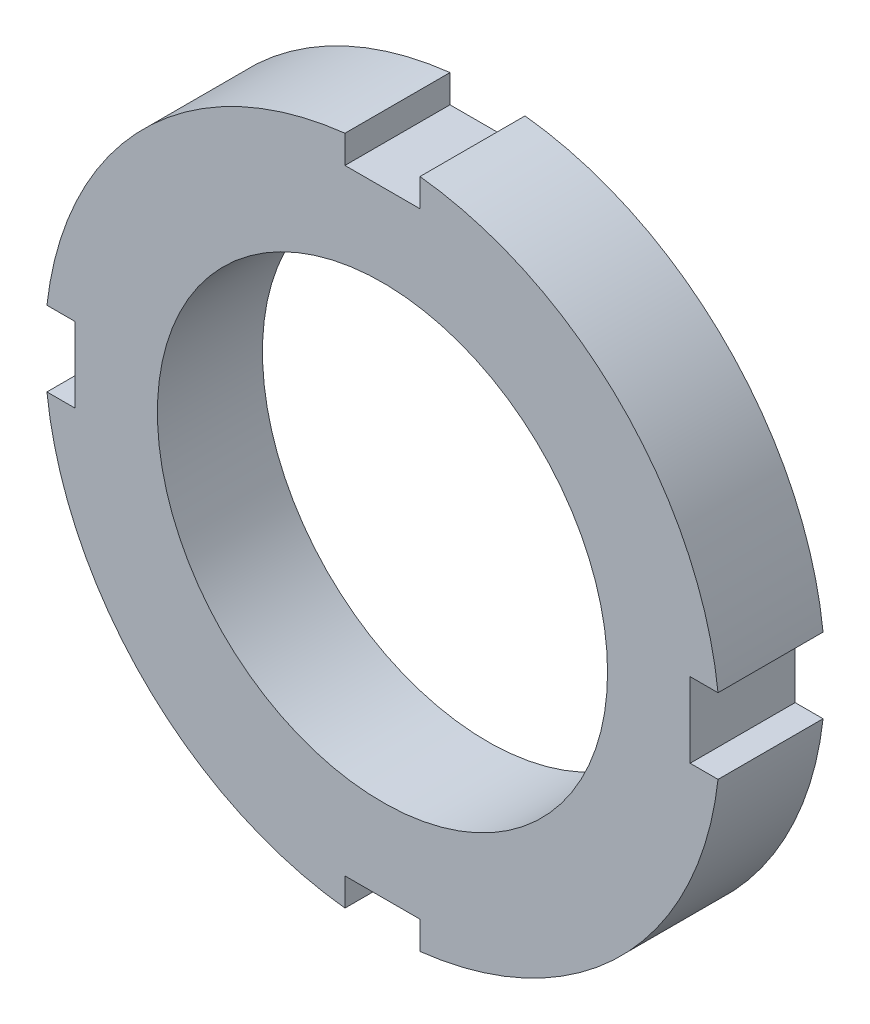
SolidWorks part; units mm, degrees
material "1.0503 (C45)"
ref_plane "Front Plane" through (0, 0, 0) normal (0, 0, 1) x (1, 0, 0)
ref_plane "Top Plane" through (0, 0, 0) normal (0, 1, 0) x (1, 0, 0)
ref_plane "Right Plane" through (0, 0, 0) normal (1, 0, 0) x (0, 0, -1)
sketch "Sketch1" plane through (0, 0, 0) normal (0, 1, 0) x (1, 0, 0)
  line L0 (15, 89) -> (22.5, 89)
  line L1 (22.5, 89) -> (22.5, 96)
  line L2 (22.5, 96) -> (15, 96)
  line L3 (15, 96) -> (15, 89)
  line L4 (0, -150) -> (0, 150) construction
revolve "REV_KM6_M30x1.5_45x7" add sketch "Sketch1" angle 360 about L4
sketch "Sketch2" plane through (0, 0, 0) normal (0, 0, 1) x (1, 0, 0)
  line L1 (20.5, -2.5) -> (23.5, -2.5)
  line L2 (20.5, -2.5) -> (20.5, 2.5)
  line L3 (20.5, 2.5) -> (23.5, 2.5)
  line L4 (23.5, -2.5) -> (23.5, 2.5)
  line L6 (-23.5, -2.5) -> (-20.5, -2.5)
  line L7 (-23.5, -2.5) -> (-23.5, 2.5)
  line L8 (-23.5, 2.5) -> (-20.5, 2.5)
  line L9 (-20.5, -2.5) -> (-20.5, 2.5)
  line L11 (-2.5, 20.5) -> (2.5, 20.5)
  line L12 (-2.5, 20.5) -> (-2.5, 23.5)
  line L13 (-2.5, 23.5) -> (2.5, 23.5)
  line L14 (2.5, 20.5) -> (2.5, 23.5)
  line L16 (-2.5, -23.5) -> (2.5, -23.5)
  line L17 (-2.5, -23.5) -> (-2.5, -20.5)
  line L18 (-2.5, -20.5) -> (2.5, -20.5)
  line L19 (2.5, -23.5) -> (2.5, -20.5)
extrude "CUT_4xSlot_5x2" cut sketch "Sketch2" along normal mid plane 300
